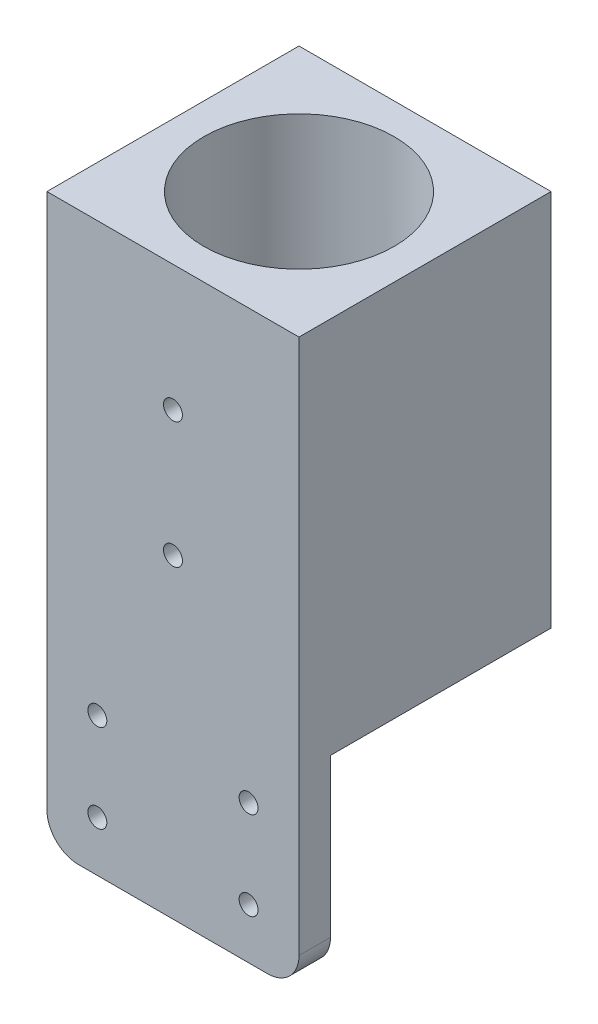
SolidWorks part; units mm, degrees
ref_plane "前基準面" through (0, 0, 0) normal (0, 0, 1) x (1, 0, 0)
ref_plane "上基準面" through (0, 0, 0) normal (0, 1, 0) x (1, 0, 0)
ref_plane "右基準面" through (0, 0, 0) normal (1, 0, 0) x (0, 0, -1)
sketch "草圖1" plane through (0, 0, 0) normal (0, 1, 0) x (1, 0, 0)
  line L1 (-20, 20) -> (20, 20)
  line L2 (-20, 20) -> (-20, -20)
  line L3 (-20, -20) -> (20, -20)
  line L4 (20, 20) -> (20, -20)
  line L5 (-20, 20) -> (20, -20) construction
  line L6 (-20, -20) -> (20, 20) construction
  dimension "D2" = 40
extrude "填料-伸長1" add sketch "草圖1" along normal blind 60
sketch "草圖2" plane through (0, 60, 0) normal (0, 1, 0) x (1, 0, 0)
  circle A0 centre (0, 0) radius 15.1
  dimension "D1" = 30.2
extrude "除料-伸長1" cut sketch "草圖2" against normal blind 50
sketch "草圖3" plane through (0, 0, 20) normal (0, 0, 1) x (1, 0, 0)
  line L1 (20, 60) -> (20, 0) construction
  line L2 (-20, 0) -> (20, 0)
  line L3 (-20, 0) -> (-20, -30)
  line L4 (-20, -30) -> (20, -30)
  line L5 (20, 0) -> (20, -30)
  line L6 (-12, -8) -> (49988, -8) construction
  line L7 (-12, -8) -> (-12, 49992) construction
  line L8 (-12, -22) -> (49988, -22) construction
  line L9 (0, 0) -> (0, 50000) construction
  circle A5 centre (-12, -8) radius 1.5
  circle A9 centre (-12, -22) radius 1.5
  circle A10 centre (12, -22) radius 1.5
  circle A11 centre (12, -8) radius 1.5
  point P21 (0, 0)
  dimension "D1" = 30
  dimension "D2" = 3
  dimension "D3" = 8
  dimension "D4" = 8
  dimension "D5" = 8
extrude "填料-伸長2" add sketch "草圖3" against normal blind 5
fillet "圓角1" radius 5 2 edges at (20, -30, 17.5) (-20, -30, 17.5)
sketch "草圖4" plane through (0, 0, -20) normal (0, 0, -1) x (-1, 0, 0)
  circle A0 centre (0, 20) radius 1.5
  dimension "D1" = 3
  dimension "D2" = 20
extrude "除料-伸長2" cut sketch "草圖4" against normal through all
pattern_linear "直線複製排列1" count 2 spacing 20 along (0, 1, 0) of "除料-伸長2"
